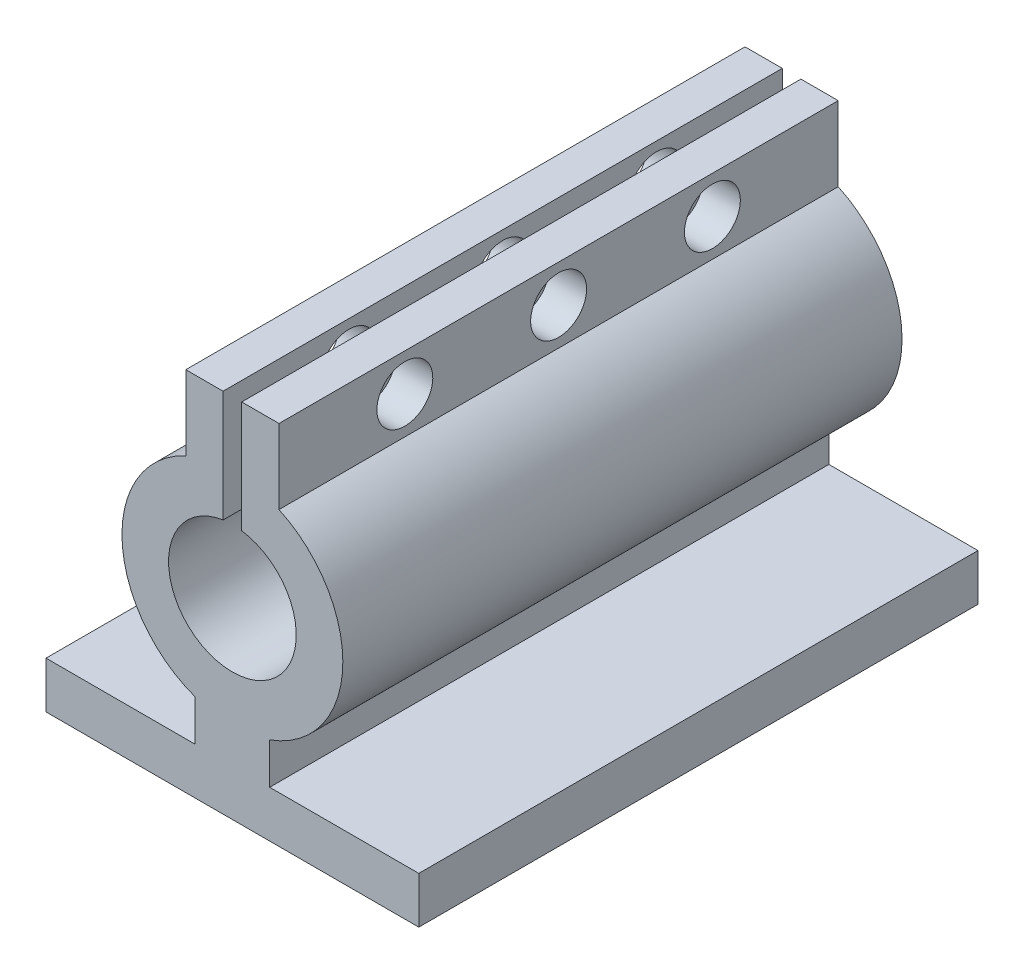
SolidWorks part; units mm, degrees
ref_plane "Front Plane" through (0, 0, 0) normal (0, 0, 1) x (1, 0, 0)
ref_plane "Top Plane" through (0, 0, 0) normal (0, 1, 0) x (1, 0, 0)
ref_plane "Right Plane" through (0, 0, 0) normal (1, 0, 0) x (0, 0, -1)
sketch "Esquisse1" plane through (0, 0, 0) normal (0, 1, 0) x (1, 0, 0)
  line L1 (0, 0) -> (40, 0)
  line L2 (0, 0) -> (0, 60)
  line L3 (0, 60) -> (40, 60)
  line L4 (40, 0) -> (40, 60)
  dimension "D1" = 40
  dimension "D2" = 60
extrude "Boss.-Extru.1" add sketch "Esquisse1" along normal blind 5
sketch "Esquisse3" plane through (0, 0, -60) normal (0, 0, 1) x (1, 0, 0)
  line L0 (16, 5) -> (16, 15)
  line L1 (0, 5) -> (40, 5) construction
  line L2 (24, 5) -> (24, 15)
  line L3 (16, 5) -> (24, 5)
  arc A3 (16, 15) -> (24, 15) centre (20, 20.5608) ccw
  point P4 (0, 0)
  point P5 (24.1557, 15)
  point P9 (20, 5)
  point P10 (20, 5)
  dimension "D2" = 6.85
  dimension "D1" = 8
  dimension "D3" = 10
extrude "Boss.-Extru.3" add sketch "Esquisse3" along normal up to surface (60 mm away) up to face at (20, 2.5, 0)
sketch "Esquisse4" plane through (0, 0, 0) normal (0, 0, 1) x (1, 0, 0)
  line L0 (15, 31.3043) -> (15, 39.3043)
  line L1 (15, 39.3043) -> (19, 39.3043)
  line L4 (21, 39.3043) -> (25, 39.3043)
  line L5 (25, 39.3043) -> (25, 31.3043)
  line L6 (20, 27.6606) -> (20, 13.8606) construction
  line L9 (19, 39.3043) -> (19, 27.3374)
  line L10 (21, 39.3043) -> (21, 27.3374)
  arc A0 (15, 31.3043) -> (25, 31.3043) centre (20, 20.5608) ccw
  arc A1 (16, 15) -> (24, 15) centre (20, 20.5608) ccw construction
  arc A2 (19, 27.3374) -> (21, 27.3374) centre (20, 20.5608) ccw
  point P1 (11.4782, 37.2213)
  point P3 (23.3, 20.4081)
  dimension "D3" = 5
  dimension "D1" = 8
  dimension "D2" = 4
  dimension "D4" = 2
extrude "Boss.-Extru.5" add sketch "Esquisse4" against normal up to surface (60 mm away) up to face at (20, 6.0889, -60)
sketch "Esquisse5" plane through (25, 0, 0) normal (1, 0, 0) x (0, 0, -1)
  line L0 (0, 35.3043) -> (10.5, 35.3043) construction
  line L5 (16.5, 35.3043) -> (27, 35.3043) construction
  line L6 (33, 35.3043) -> (43.5, 35.3043) construction
  line L8 (49.5, 35.3043) -> (60, 35.3043) construction
  line L10 (60, 39.3043) -> (60, 31.3043) construction
  line L11 (0, 31.3043) -> (0, 39.3043) construction
  circle A0 centre (13.5, 35.3043) radius 3
  circle A1 centre (30, 35.3043) radius 3
  circle A2 centre (46.5, 35.3043) radius 3
  point P8 (0, 36.121)
  point P16 (60, 34.7435)
  dimension "D1" = 6
extrude "Enlèv. mat.-Extru.1" cut sketch "Esquisse5" against normal through all
